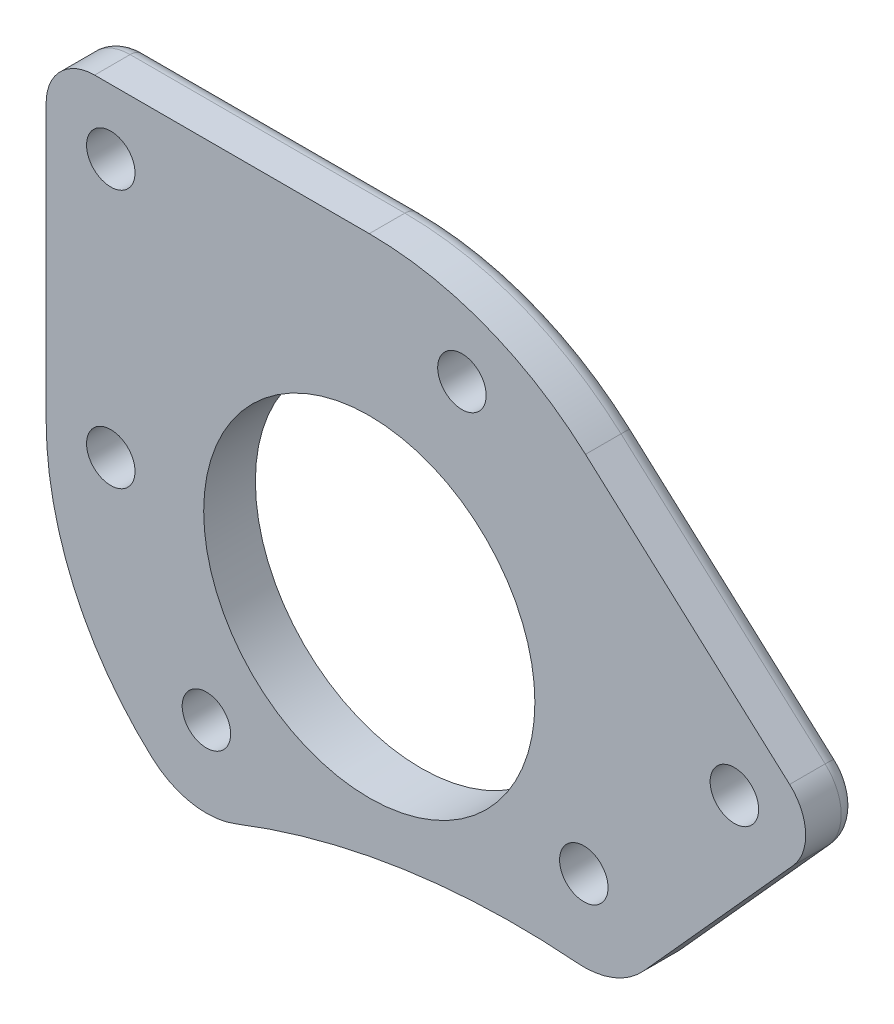
SolidWorks part; units mm, degrees
material "尼龙 101"
ref_plane "前视基准面" through (0, 0, 0) normal (0, 0, 1) x (1, 0, 0)
ref_plane "上视基准面" through (0, 0, 0) normal (0, 1, 0) x (1, 0, 0)
ref_plane "右视基准面" through (0, 0, 0) normal (1, 0, 0) x (0, 0, -1)
sketch "草图1" plane through (0, 0, 0) normal (0, 0, 1) x (1, 0, 0)
  line L0 (4.334, 74.8629) -> (16.9675, 63.4877) construction
  line L1 (17.1895, 59.2508) -> (7.945, 48.9837) construction
  line L2 (-29.0486, 60) -> (-29.0486, 77) construction
  line L3 (-26.0486, 80) -> (-9.0486, 80) construction
  line L4 (4.334, 74.8629) -> (16.9675, 63.4877)
  line L5 (17.1895, 59.2508) -> (7.945, 48.9837)
  line L6 (-29.0486, 60) -> (-29.0486, 77)
  line L7 (-26.0486, 80) -> (-9.0486, 80)
  arc A0 (4.334, 74.8629) -> (-9.0486, 80) centre (-9.0486, 60) ccw construction
  arc A1 (17.1895, 59.2508) -> (16.9675, 63.4877) centre (14.9601, 61.2582) ccw construction
  arc A2 (3.8264, 47.3456) -> (7.945, 48.9837) centre (4.2292, 52.3294) ccw construction
  arc A3 (3.8264, 47.3456) -> (-17.3064, 44.235) centre (0, 0) ccw construction
  arc A4 (-22.488, 45.1885) -> (-17.3064, 44.235) centre (-19.1282, 48.8913) ccw construction
  arc A5 (-29.0486, 60) -> (-22.488, 45.1885) centre (-9.0486, 60) ccw construction
  arc A6 (-26.0486, 80) -> (-29.0486, 77) centre (-26.0486, 77) ccw construction
  arc A7 (4.334, 74.8629) -> (-9.0486, 80) centre (-9.0486, 60) ccw
  arc A8 (17.1895, 59.2508) -> (16.9675, 63.4877) centre (14.9601, 61.2582) ccw
  arc A9 (3.8264, 47.3456) -> (7.945, 48.9837) centre (4.2292, 52.3294) ccw
  arc A10 (3.8264, 47.3456) -> (-17.3064, 44.235) centre (0, 0) ccw
  arc A11 (-22.488, 45.1885) -> (-17.3064, 44.235) centre (-19.1282, 48.8913) ccw
  arc A12 (-29.0486, 60) -> (-22.488, 45.1885) centre (-9.0486, 60) ccw
  arc A13 (-26.0486, 80) -> (-29.0486, 77) centre (-26.0486, 77) ccw
  circle A15 centre (-9.0486, 60) radius 10.25
  circle A16 centre (-9.0486, 60) radius 10.25
  circle A17 centre (-25.0486, 76) radius 1.5
  circle A18 centre (-25.0486, 76) radius 1.5
  circle A19 centre (-3.3147, 74.9373) radius 1.5
  circle A20 centre (-3.3147, 74.9373) radius 1.5
  circle A21 centre (-25.0486, 60) radius 1.5
  circle A22 centre (-25.0486, 60) radius 1.5
  circle A23 centre (-19.1282, 48.8913) radius 1.5
  circle A24 centre (-19.1282, 48.8913) radius 1.5
  circle A25 centre (4.2292, 52.3294) radius 1.5
  circle A26 centre (4.2292, 52.3294) radius 1.5
  circle A27 centre (13.5478, 61.1842) radius 1.5
  circle A28 centre (13.5478, 61.1842) radius 1.5
  dimension "D1" = 0
  dimension "D2" = 0
  dimension "D3" = 0
  dimension "D4" = 0
  dimension "D5" = 0
  dimension "D6" = 0
  dimension "D7" = 0
extrude "凸台-拉伸1" add sketch "草图1" along normal blind 3.2
fillet "圆角1" radius 1
